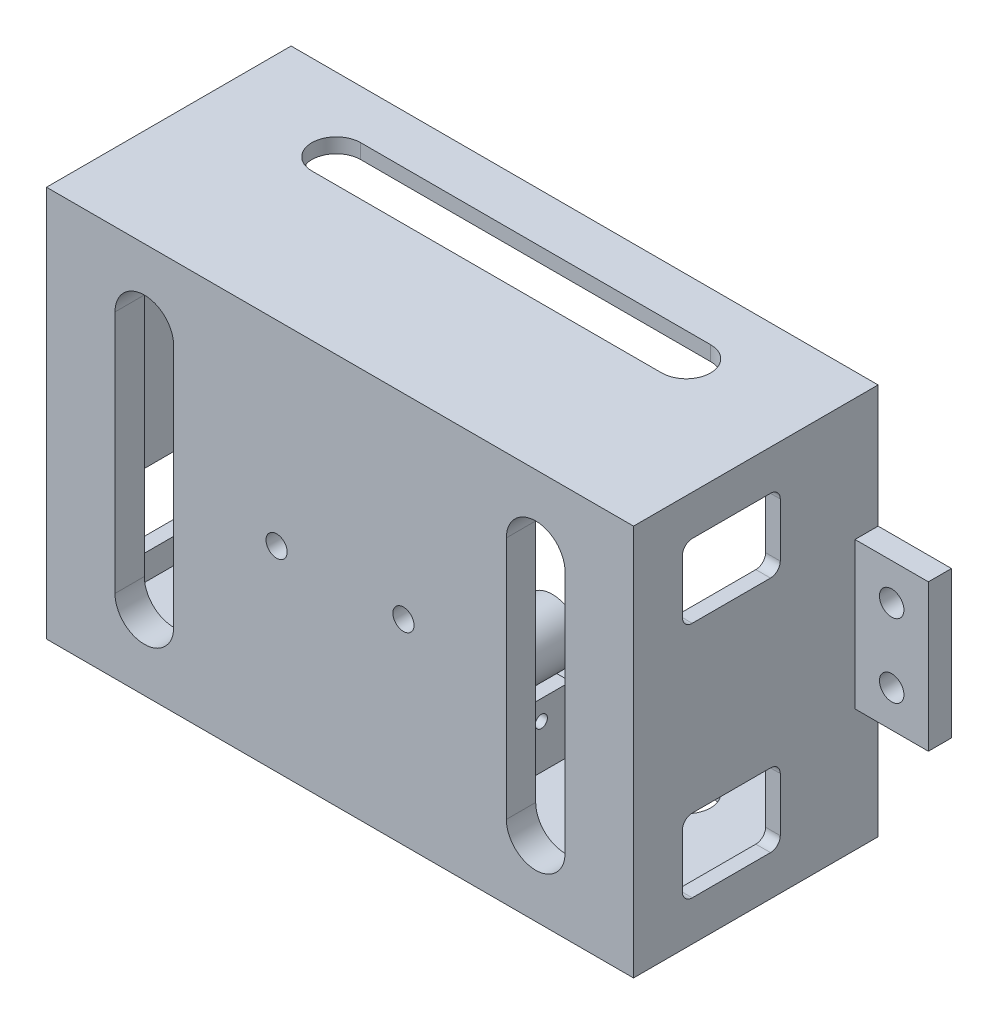
SolidWorks part; units mm, degrees
ref_plane "Front Plane" through (0, 0, 0) normal (0, 0, 1) x (1, 0, 0)
ref_plane "Top Plane" through (0, 0, 0) normal (0, 1, 0) x (1, 0, 0)
ref_plane "Right Plane" through (0, 0, 0) normal (1, 0, 0) x (0, 0, -1)
sketch "Sketch1" plane through (0, 0, 0) normal (0, 0, 1) x (1, 0, 0)
  line L1 (-60, 40) -> (60, 40)
  line L2 (-60, 40) -> (-60, -40)
  line L3 (-60, -40) -> (60, -40)
  line L4 (60, 40) -> (60, -40)
  line L5 (-60, 40) -> (60, -40) construction
  line L6 (-60, -40) -> (60, 40) construction
  point P0 (0, 0)
  dimension "D1" = 120
  dimension "D2" = 80
extrude "Boss-Extrude1" add sketch "Sketch1" along normal blind 60
shell "Shell3" thickness 6
sketch "Sketch2" plane through (60, 0, 0) normal (1, 0, 0) x (0, 0, -1)
  line L0 (-60, 40) -> (0, 40) construction
  line L1 (-4.7224, 15) -> (0, 15)
  line L2 (-4.7224, 15) -> (-4.7224, -15)
  line L3 (-4.7224, -15) -> (0, -15)
  line L5 (-4.7224, 15) -> (0, 0) construction
  line L6 (-4.7224, -15) -> (0, 0) construction
  line L7 (0, 15) -> (0, -15) construction
  line L8 (0, 15) -> (0, -15)
  line L9 (0, 0) -> (0, 15) construction
  line L10 (0, 0) -> (0, -15) construction
  line L11 (0, 0) -> (-4.7224, 0) construction
  point P0 (0, 0)
  dimension "D1" = 30
  dimension "D2" = 40
  dimension "D3" = 15
  dimension "D4" = 15
extrude "Boss-Extrude2" add sketch "Sketch2" along normal blind 15
sketch "Sketch3" plane through (-60, 0, 0) normal (-1, 0, 0) x (0, 0, 1)
  line L0 (0, 15) -> (0, -15)
  line L1 (0, 15) -> (5, 15)
  line L3 (0, -15) -> (5, -15)
  line L4 (5, 15) -> (5, -15)
  line L5 (0, 0) -> (5, -15) construction
  line L6 (0, 0) -> (5, 15) construction
  point P0 (0, 0)
  dimension "D3" = 15
extrude "Boss-Extrude3" add sketch "Sketch3" along normal blind 15
sketch "Sketch4" plane through (0, 0, 5) normal (0, 0, 1) x (1, 0, 0)
  line L0 (-67.5, 7.5) -> (-75, 7.5) construction
  line L1 (-75, -15) -> (-75, 15) construction
  line L2 (-67.5, -7.5) -> (-75, -7.5) construction
  line L3 (-75, 15) -> (-60, 15) construction
  line L4 (-75, -15) -> (-60, -15) construction
  line L5 (0, -58.7244) -> (0, 61.6528) construction
  circle A0 centre (-67.5, 7.5) radius 2.5
  circle A1 centre (-67.5, -7.5) radius 2.5
  circle A2 centre (67.5, -7.5) radius 2.5
  circle A3 centre (67.5, 7.5) radius 2.5
  dimension "D1" = 5
  dimension "D2" = 5
  dimension "D3" = 7.5
  dimension "D4" = 7.5
  dimension "D5" = 7.5
  dimension "D6" = 7.5
extrude "Cut-Extrude2" cut sketch "Sketch4" against normal up to surface (5 mm away) up to face at (0, 0, 0)
sketch "Sketch5" plane through (60, 0, 0) normal (1, 0, 0) x (0, 0, -1)
  line L1 (-38, 31.8029) -> (-22, 31.8029)
  line L2 (-40, 29.8029) -> (-40, 18.8029)
  line L3 (-38, 16.8029) -> (-22, 16.8029)
  line L4 (-20, 29.8029) -> (-20, 18.8029)
  line L5 (-40, 31.8029) -> (-20, 16.8029) construction
  line L6 (-40, 16.8029) -> (-20, 31.8029) construction
  line L11 (-40, -16.8029) -> (-20, -31.8029) construction
  line L12 (-40, -31.8029) -> (-20, -16.8029) construction
  line L13 (20.2127, 0) -> (-80.5303, 0) construction
  line L14 (-60, 40) -> (0, 40) construction
  line L15 (-30, 24.3029) -> (0, 24.3029) construction
  line L16 (0, 15) -> (0, 40) construction
  line L17 (-20, -29.8029) -> (-20, -18.8029)
  line L18 (-38, -16.8029) -> (-22, -16.8029)
  line L19 (-40, -29.8029) -> (-40, -18.8029)
  line L20 (-38, -31.8029) -> (-22, -31.8029)
  arc A0 (-38, -31.8029) -> (-40, -29.8029) centre (-38, -29.8029) cw
  arc A1 (-22, -31.8029) -> (-20, -29.8029) centre (-22, -29.8029) ccw
  arc A2 (-22, -16.8029) -> (-20, -18.8029) centre (-22, -18.8029) cw
  arc A3 (-40, -18.8029) -> (-38, -16.8029) centre (-38, -18.8029) cw
  arc A4 (-38, 31.8029) -> (-40, 29.8029) centre (-38, 29.8029) ccw
  arc A5 (-40, 18.8029) -> (-38, 16.8029) centre (-38, 18.8029) ccw
  arc A6 (-22, 16.8029) -> (-20, 18.8029) centre (-22, 18.8029) ccw
  arc A7 (-22, 31.8029) -> (-20, 29.8029) centre (-22, 29.8029) cw
  point P0 (-30, 24.3029)
  point P9 (-30, -24.3029)
  dimension "D5" = 2
  dimension "D1" = 20
  dimension "D2" = 15
  dimension "D3" = 15.6971
  dimension "D4" = 15.6971
extrude "Cut-Extrude3" cut sketch "Sketch5" against normal up to surface (120 mm away) up to face at (-60, 0, 16.25)
sketch "Sketch6" plane through (0, 0, 60) normal (0, 0, 1) x (1, 0, 0)
  line L0 (-40, 24.9189) -> (-40, -24.9189) construction
  line L1 (-34, 24.9189) -> (-34, -24.9189)
  line L2 (-46, 24.9189) -> (-46, -24.9189)
  line L3 (107.6356, 0) -> (-102.4442, 0) construction
  line L4 (-60, 40) -> (-60, -40) construction
  line L5 (0, 60.5667) -> (0, -59.5284) construction
  line L6 (40, 24.9189) -> (40, -24.9189) construction
  line L7 (34, 24.9189) -> (34, -24.9189)
  line L8 (46, 24.9189) -> (46, -24.9189)
  arc A0 (-34, 24.9189) -> (-46, 24.9189) centre (-40, 24.9189) ccw
  arc A1 (-46, -24.9189) -> (-34, -24.9189) centre (-40, -24.9189) ccw
  arc A2 (34, 24.9189) -> (46, 24.9189) centre (40, 24.9189) cw
  arc A3 (46, -24.9189) -> (34, -24.9189) centre (40, -24.9189) cw
  point P2 (-40, 0)
  point P12 (40, 0)
  dimension "D2" = 6
  dimension "D1" = 20
extrude "Cut-Extrude4" cut sketch "Sketch6" against normal up to surface (6 mm away) up to face at (0, 0, 54)
sketch "Sketch7" plane through (0, 0, 54) normal (0, 0, -1) x (-1, 0, 0)
  line L0 (0, 58.144) -> (0, -58.8362) construction
  line L1 (-104.5207, 0) -> (108.6739, 0) construction
  circle A0 centre (-12.965, 0) radius 2.16
  circle A1 centre (12.965, 0) radius 2.16
  dimension "D3" = 4.32
  dimension "D4" = 4.32
  dimension "D2" = 25.93
  dimension "D5" = 12.965
extrude "Cut-Extrude5" cut sketch "Sketch7" against normal up to surface (6 mm away) up to face at (-40, 0, 60)
sketch "Sketch9" plane through (0, 0, 54) normal (0, 0, -1) x (-1, 0, 0)
  line L4 (-54, 34) -> (-54, -34)
  line L5 (-54, -34) -> (54, -34)
  line L6 (54, -34) -> (54, 34)
  line L7 (54, 34) -> (-54, 34)
  line L8 (-54, 34) -> (-54, -34)
  line L9 (-54, -34) -> (54, -34)
  line L10 (54, -34) -> (54, 34)
  line L11 (54, 34) -> (-54, 34)
  dimension "D1" = 0
extrude "Boss-Extrude4" add sketch "Sketch9" along normal blind 10
sketch "Sketch12" plane through (0, 0, 54) normal (0, 0, 1) x (1, 0, 0)
  line L0 (46, -24.9189) -> (46, 24.9189) construction
  line L1 (34, 24.9189) -> (34, -24.9189) construction
  line L2 (-34, -24.9189) -> (-34, 24.9189) construction
  line L3 (-46, 24.9189) -> (-46, -24.9189) construction
  line L4 (46, -24.9189) -> (46, 24.9189)
  line L5 (34, 24.9189) -> (34, -24.9189)
  line L6 (-34, -24.9189) -> (-34, 24.9189)
  line L7 (-46, 24.9189) -> (-46, -24.9189)
  arc A0 (46, 24.9189) -> (34, 24.9189) centre (40, 24.9189) ccw construction
  arc A1 (34, -24.9189) -> (46, -24.9189) centre (40, -24.9189) ccw construction
  circle A2 centre (12.965, 0) radius 2.16 construction
  circle A3 centre (-12.965, 0) radius 2.16 construction
  arc A4 (-34, 24.9189) -> (-46, 24.9189) centre (-40, 24.9189) ccw construction
  arc A5 (-46, -24.9189) -> (-34, -24.9189) centre (-40, -24.9189) ccw construction
  arc A6 (46, 24.9189) -> (34, 24.9189) centre (40, 24.9189) ccw
  arc A7 (34, -24.9189) -> (46, -24.9189) centre (40, -24.9189) ccw
  circle A8 centre (12.965, 0) radius 2.16
  circle A9 centre (-12.965, 0) radius 2.16
  arc A10 (-34, 24.9189) -> (-46, 24.9189) centre (-40, 24.9189) ccw
  arc A11 (-46, -24.9189) -> (-34, -24.9189) centre (-40, -24.9189) ccw
extrude "Cut-Extrude6" cut sketch "Sketch12" against normal up to surface (10 mm away) up to face at (0, 0, 44)
sketch "Sketch13" plane through (0, 0, 60) normal (0, 0, 1) x (1, 0, 0)
  line L4 (60, -40) -> (60, 40)
  line L5 (60, 40) -> (-60, 40)
  line L6 (-60, 40) -> (-60, -40)
  line L7 (-60, -40) -> (60, -40)
  line L8 (60, -40) -> (60, 40)
  line L9 (60, 40) -> (-60, 40)
  line L10 (-60, 40) -> (-60, -40)
  line L11 (-60, -40) -> (60, -40)
  dimension "D1" = 0
extrude "Cut-Extrude7" cut sketch "Sketch13" against normal blind 10
sketch "Sketch14" plane through (0, 40, 0) normal (0, 1, 0) x (1, 0, 0)
  line L0 (-35.7632, -15) -> (35.7632, -15) construction
  line L1 (-35.7632, -10) -> (35.7632, -10)
  line L2 (-35.7632, -20) -> (35.7632, -20)
  line L3 (60, 0) -> (-60, 0) construction
  line L4 (0, 0) -> (0, -15) construction
  line L5 (60, -50) -> (60, 0) construction
  arc A0 (-35.7632, -10) -> (-35.7632, -20) centre (-35.7632, -15) ccw
  arc A1 (35.7632, -20) -> (35.7632, -10) centre (35.7632, -15) ccw
  point P2 (0, -15)
  dimension "D2" = 5
  dimension "D1" = 10
extrude "Cut-Extrude8" cut sketch "Sketch14" against normal up to surface (80 mm away) up to face at (0, -40, 25)
sketch "Sketch17" plane through (0, 0, 0) normal (0, 0, -1) x (-1, 0, 0)
  line L0 (-54, -34) -> (-54, 34) construction
  line L1 (-54, 34) -> (54, 34) construction
  line L2 (54, 34) -> (54, -34) construction
  line L4 (54, -34) -> (-54, -34) construction
  line L5 (54, -34) -> (-54, -34)
  line L6 (54, 34) -> (54, -34)
  line L7 (-54, -34) -> (-54, 34)
  line L8 (57, -37) -> (57, 37)
  line L9 (-57, -37) -> (57, -37)
  line L10 (-57, 37) -> (-57, -37)
  line L11 (57, 37) -> (-57, 37)
  line L12 (57, -37) -> (57, 37)
  line L13 (-57, -37) -> (57, -37)
  line L14 (-57, 37) -> (-57, -37)
  line L15 (57, 37) -> (-57, 37)
  line L16 (-54, 34) -> (54, 34)
  dimension "D1" = 3
extrude "Cut-Extrude9" cut sketch "Sketch17" against normal up to surface (44 mm away) contours L12 L15 L14 L13 | L5 L7 L16 L6
sketch "Sketch23" plane through (0, 0, 44) normal (0, 0, -1) x (-1, 0, 0)
  line L14 (-18.7312, 0) -> (37.4198, 0) construction
  line L15 (0, 21.3162) -> (0, -15.8761) construction
  line L24 (-17.15, 14.35) -> (-17.15, 5)
  line L25 (-17.15, 5) -> (-14.15, 5)
  line L26 (-14.15, 5) -> (-14.15, 11.35)
  line L30 (17.15, 14.35) -> (17.15, 5)
  line L31 (17.15, 5) -> (14.15, 5)
  line L32 (14.15, 5) -> (14.15, 11.35)
  line L34 (-17.15, 14.35) -> (17.15, 14.35)
  line L35 (14.15, 11.35) -> (-14.15, 11.35)
  dimension "D1" = 11.35
  dimension "D2" = 3
  dimension "D3" = 5
  dimension "D4" = 5
extrude "Boss-Extrude5" add sketch "Sketch23" along normal blind 10
sketch "Sketch24" plane through (0, 0, 44) normal (0, 0, -1) x (-1, 0, 0)
  line L1 (-4.1985, 9.3641) -> (4.1985, 9.3641)
  line L2 (-4.1985, 9.3641) -> (-4.1985, -9.3641)
  line L3 (-4.1985, -9.3641) -> (4.1985, -9.3641)
  line L4 (4.1985, 9.3641) -> (4.1985, -9.3641)
  line L5 (-4.1985, 9.3641) -> (4.1985, -9.3641) construction
  line L6 (-4.1985, -9.3641) -> (4.1985, 9.3641) construction
  point P0 (0, 0)
extrude "Boss-Extrude6" add sketch "Sketch24" along normal blind 5
sketch "Sketch28" plane through (0, 0, 44) normal (0, 0, -1) x (-1, 0, 0)
  line L0 (0, 0) -> (0, -46.805) construction
  line L1 (-14.15, 5) -> (-14.15, 11.35) construction
  line L2 (-14.15, -37) -> (-17.15, -37)
  line L3 (-14.15, -37) -> (-14.15, -23.945)
  line L4 (-14.15, -23.945) -> (-17.15, -23.945)
  line L5 (-17.15, -37) -> (-17.15, -23.945)
  line L6 (-57, -37) -> (57, -37) construction
  line L7 (14.15, -23.945) -> (17.15, -23.945)
  line L8 (17.15, -37) -> (17.15, -23.945)
  line L9 (14.15, -37) -> (17.15, -37)
  line L10 (14.15, -37) -> (14.15, -23.945)
  dimension "D1" = 0
  dimension "D2" = 0
  dimension "D3" = 3
extrude "Boss-Extrude8" add sketch "Sketch28" along normal up to surface (24 mm away) up to face at (0, -38.5, 20)
sketch "Sketch29" plane through (-17.15, 0, 0) normal (-1, 0, 0) x (0, 0, 1)
  line L0 (20, -37) -> (44, -37) construction
  line L1 (44, -37) -> (44, -23.945) construction
  line L2 (20, -37) -> (44, -37) construction
  line L3 (44, -37) -> (44, -23.945) construction
  circle A1 centre (26, -28) radius 1.25
  dimension "D3" = 2.5
  dimension "D1" = 18
  dimension "D2" = 9
extrude "Cut-Extrude10" cut sketch "Sketch29" against normal blind 48
sketch "Sketch30" plane through (0, 0, 44) normal (0, 0, -1) x (-1, 0, 0)
  circle A0 centre (-25.4, -4.36) radius 3
  circle A1 centre (25.4, 4.36) radius 3
  circle A2 centre (-25.4, -4.36) radius 6
  circle A3 centre (25.4, 4.36) radius 6
  point P6 (0, 0)
  dimension "D1" = 6
  dimension "D2" = 6
  dimension "D7" = 12
  dimension "D8" = 12
  dimension "D3" = 25.4
  dimension "D4" = 25.4
  dimension "D5" = 4.36
  dimension "D6" = 4.36
extrude "Boss-Extrude9" add sketch "Sketch30" along normal blind 10
sketch "Sketch31" plane through (0, 0, 34) normal (0, 0, -1) x (-1, 0, 0)
  circle A0 centre (-25.4, -4.36) radius 6
  circle A1 centre (25.4, 4.36) radius 6
  circle A2 centre (-25.4, -4.36) radius 1.5
  circle A3 centre (25.4, 4.36) radius 1.5
  dimension "D1" = 3
  dimension "D2" = 3
extrude "Boss-Extrude10" add sketch "Sketch31" along normal blind 2
